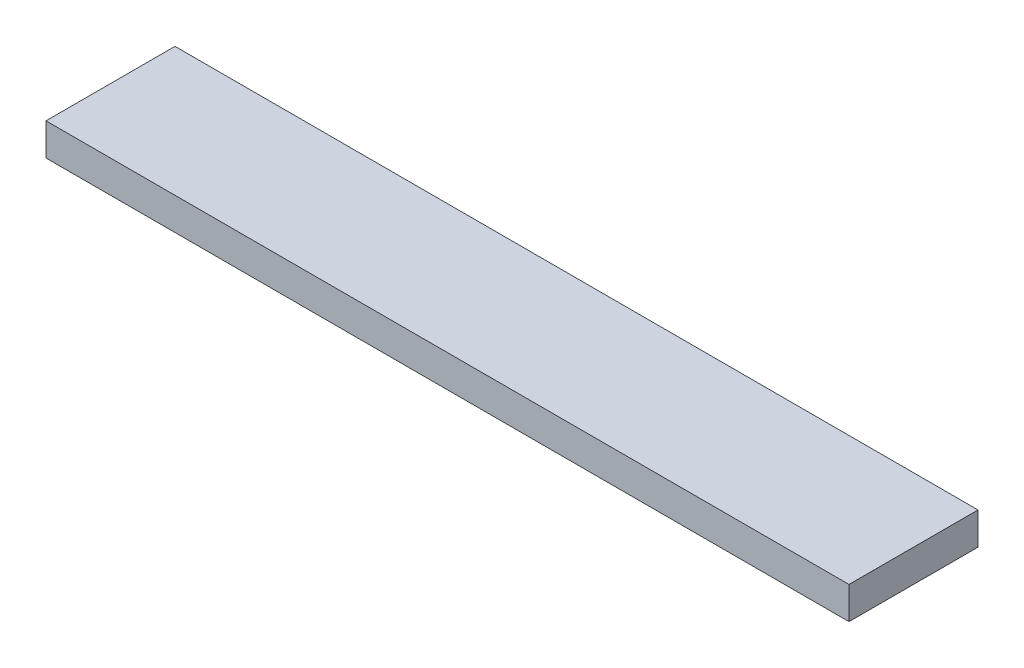
SolidWorks part; units mm, degrees
ref_plane "정면" through (0, 0, 0) normal (0, 0, 1) x (1, 0, 0)
ref_plane "윗면" through (0, 0, 0) normal (0, 1, 0) x (1, 0, 0)
ref_plane "우측면" through (0, 0, 0) normal (1, 0, 0) x (0, 0, -1)
sketch "스케치1" plane through (0, 0, 0) normal (0, 1, 0) x (1, 0, 0)
  line L1 (0, 0) -> (124.5, 0)
  line L2 (0, 0) -> (0, 20)
  line L3 (0, 20) -> (124.5, 20)
  line L4 (124.5, 0) -> (124.5, 20)
  dimension "D1" = 20
  dimension "D2" = 124.5
extrude "보스-돌출1" add sketch "스케치1" along normal blind 5
